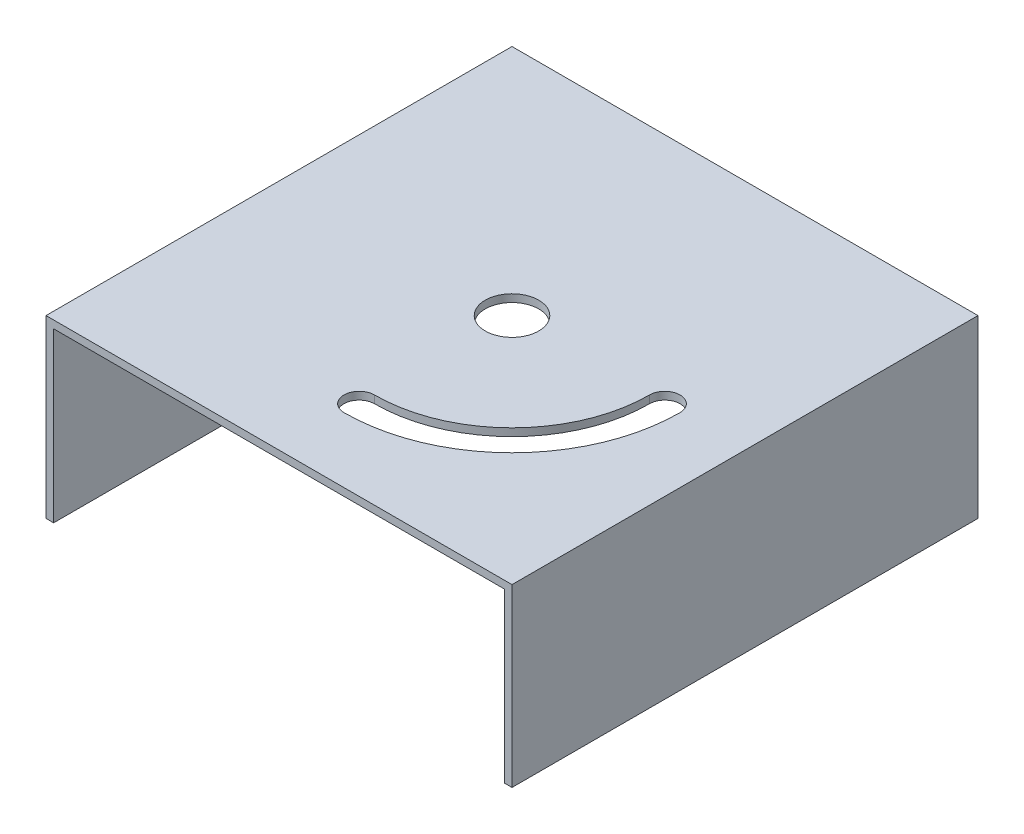
SolidWorks part; units mm, degrees
material "AISI 1020"
ref_plane "Ön Düzlem" through (0, 0, 0) normal (0, 0, 1) x (1, 0, 0)
ref_plane "Üst Düzlem" through (0, 0, 0) normal (0, 1, 0) x (1, 0, 0)
ref_plane "Sağ Düzlem" through (0, 0, 0) normal (1, 0, 0) x (0, 0, -1)
sketch "Çizim1" plane through (0, 0, 0) normal (0, 0, 1) x (1, 0, 0)
  line L0 (0, 0) -> (0, 200)
  line L1 (0, 200) -> (610, 200)
  line L2 (610, 200) -> (610, 0)
  line L3 (10, 0) -> (10, 190)
  line L4 (10, 190) -> (600, 190)
  line L5 (600, 190) -> (600, 0)
  line L6 (0, 0) -> (10, 0)
  line L7 (600, 0) -> (610, 0)
  dimension "D2" = 610
  dimension "D3" = 200
  dimension "D4" = 200
  dimension "D1" = 10
extrude "Yükseklik-Ekstrüzyon1" add sketch "Çizim1" along normal blind 610
sketch "Çizim2" plane through (0, 200, 0) normal (0, 1, 0) x (1, 0, 0)
  line L0 (305, -305) -> (305, -525) construction
  line L1 (305, -305) -> (525, -305) construction
  line L2 (525, -305) -> (505, -305)
  line L3 (305, -525) -> (305, -505)
  line L7 (0, -610) -> (0, 0) construction
  line L9 (610, -610) -> (0, -610) construction
  circle A0 centre (305, -305) radius 35
  circle A1 centre (305, -305) radius 250 construction
  circle A2 centre (305, -305) radius 220 construction
  circle A3 centre (305, -305) radius 200 construction
  arc A4 (305, -505) -> (505, -305) centre (305, -305) ccw construction
  arc A5 (305, -525) -> (525, -305) centre (305, -305) ccw
  arc A6 (305, -485) -> (485, -305) centre (305, -305) ccw
  arc A7 (305, -485) -> (305, -525) centre (305, -505) ccw
  arc A8 (525, -305) -> (485, -305) centre (505, -305) ccw
  point P8 (446.4214, -446.4214)
  dimension "D1" = 70
  dimension "D4" = 20
  dimension "D5" = 305
  dimension "D3" = 500
  dimension "D2" = 440
  dimension "D8" = 400
  dimension "D9" = 20
  dimension "D6" = 305
  dimension "D7" = 20
sketch "Çizim3" plane through (0, 0, 0) normal (0, -1, 0) x (1, 0, 0)
  line L4 (0, 0) -> (10, 0)
  line L5 (10, 0) -> (10, 610)
  line L6 (10, 610) -> (0, 610)
  line L7 (0, 610) -> (0, 0)
  line L8 (0, 0) -> (10, 0)
  line L9 (10, 0) -> (10, 610)
  line L10 (10, 610) -> (0, 610)
  line L11 (0, 610) -> (0, 0)
  line L12 (600, 0) -> (610, 0)
  line L13 (610, 0) -> (610, 610)
  line L14 (610, 610) -> (600, 610)
  line L15 (600, 610) -> (600, 0)
  line L16 (600, 0) -> (610, 0)
  line L17 (610, 0) -> (610, 610)
  line L18 (610, 610) -> (600, 610)
  line L19 (600, 610) -> (600, 0)
  dimension "D1" = 0
  dimension "D2" = 0
extrude "Yükseklik-Ekstrüzyon2" add sketch "Çizim3" along normal blind 30
extrude "Kes-Ekstrüzyon1" cut sketch "Çizim2" against normal blind 10
